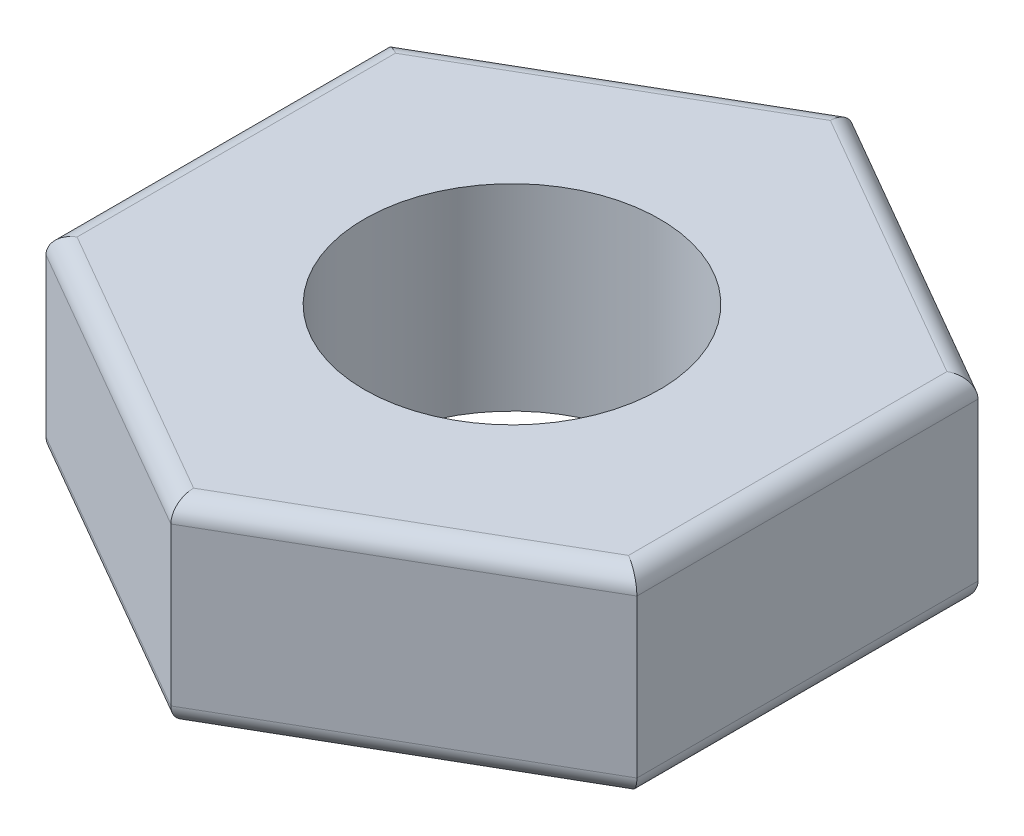
SolidWorks part; units mm, degrees
material "Nylon 101"
ref_plane "Front Plane" through (0, 0, 0) normal (0, 0, 1) x (1, 0, 0)
ref_plane "Top Plane" through (0, 0, 0) normal (0, 1, 0) x (1, 0, 0)
ref_plane "Right Plane" through (0, 0, 0) normal (1, 0, 0) x (0, 0, -1)
sketch "Sketch1" plane through (0, 0, 0) normal (0, 1, 0) x (1, 0, 0)
  line L1 (0, 6.9282) -> (-6, 3.4641)
  line L2 (-6, 3.4641) -> (-6, -3.4641)
  line L3 (-6, -3.4641) -> (0, -6.9282)
  line L4 (0, -6.9282) -> (6, -3.4641)
  line L5 (6, -3.4641) -> (6, 3.4641)
  line L6 (6, 3.4641) -> (0, 6.9282)
  circle A0 centre (0, 0) radius 3
  circle A1 centre (0, 0) radius 6 construction
  dimension "D1" = 6
  dimension "D2" = 12
extrude "Boss-Extrude1" add sketch "Sketch1" along normal blind 4
cosmetic thread "Cosmetic Thread1" parameters "D1"=4, "D2"=6.6
fillet "Fillet1" radius 0.4 12 edges at (3, 0, -5.1962) (6, 0, 0) (3, 0, 5.1962) (-3, 0, -5.1962) (-6, 0, 0) (-3, 0, 5.1962) (-6, 4, 0) (-3, 4, -5.1962) (3, 4, -5.1962) (6, 4, 0) (3, 4, 5.1962) (-3, 4, 5.1962)
